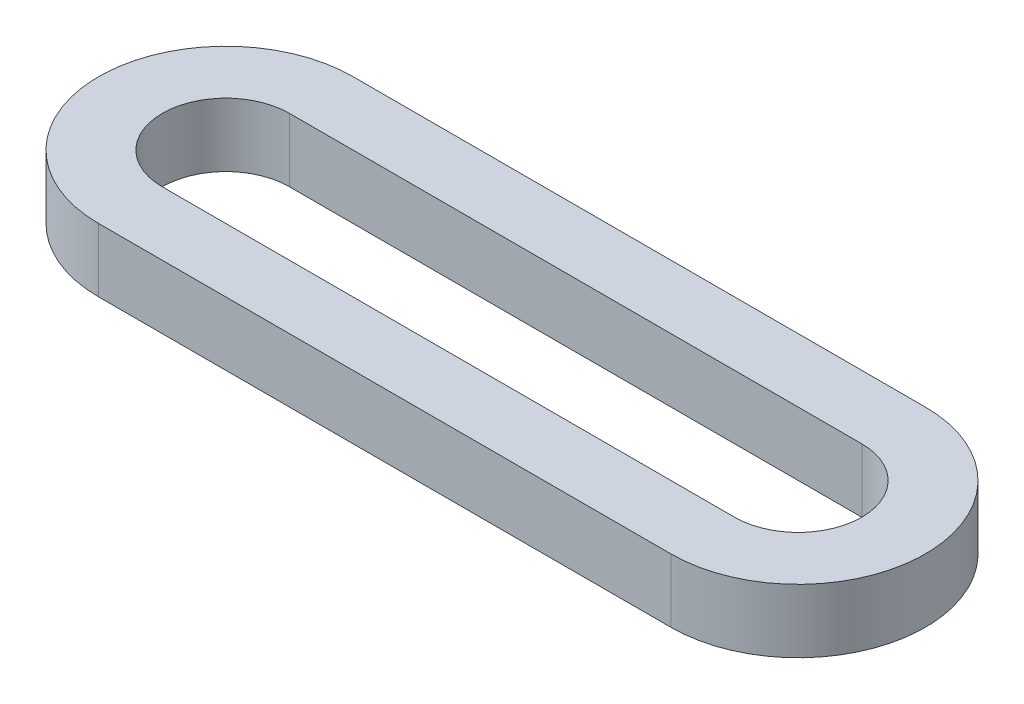
SolidWorks part; units mm, degrees
ref_plane "Front Plane" through (0, 0, 0) normal (0, 0, 1) x (1, 0, 0)
ref_plane "Top Plane" through (0, 0, 0) normal (0, 1, 0) x (1, 0, 0)
ref_plane "Right Plane" through (0, 0, 0) normal (1, 0, 0) x (0, 0, -1)
sketch "Sketch1" plane through (0, 0, 0) normal (0, 1, 0) x (1, 0, 0)
  line L0 (0, 4) -> (0, -4) construction
  line L5 (0, 0.5) -> (0, -0.5) construction
  line L8 (-9, -2) -> (-9, 2)
  line L10 (9, -2) -> (9, 2)
  line L12 (-9, 2) -> (9, 2)
  line L13 (-9, 2) -> (-9, 4)
  line L14 (-9, 4) -> (9, 4)
  line L15 (9, 2) -> (9, 4)
  line L17 (-9, -2) -> (9, -2)
  line L18 (-9, -2) -> (-9, -4)
  line L19 (-9, -4) -> (9, -4)
  line L20 (9, -2) -> (9, -4)
  circle A0 centre (-9, 0) radius 4
  circle A1 centre (-9, 0) radius 2
  circle A4 centre (9, 0) radius 4
  circle A5 centre (9, 0) radius 2
  point P9 (0, 0)
  point P20 (0, 0)
  dimension "D1" = 4
  dimension "D2" = 18
  dimension "D4" = 2
extrude "Boss-Extrude1" add sketch "Sketch1" along normal blind 2
